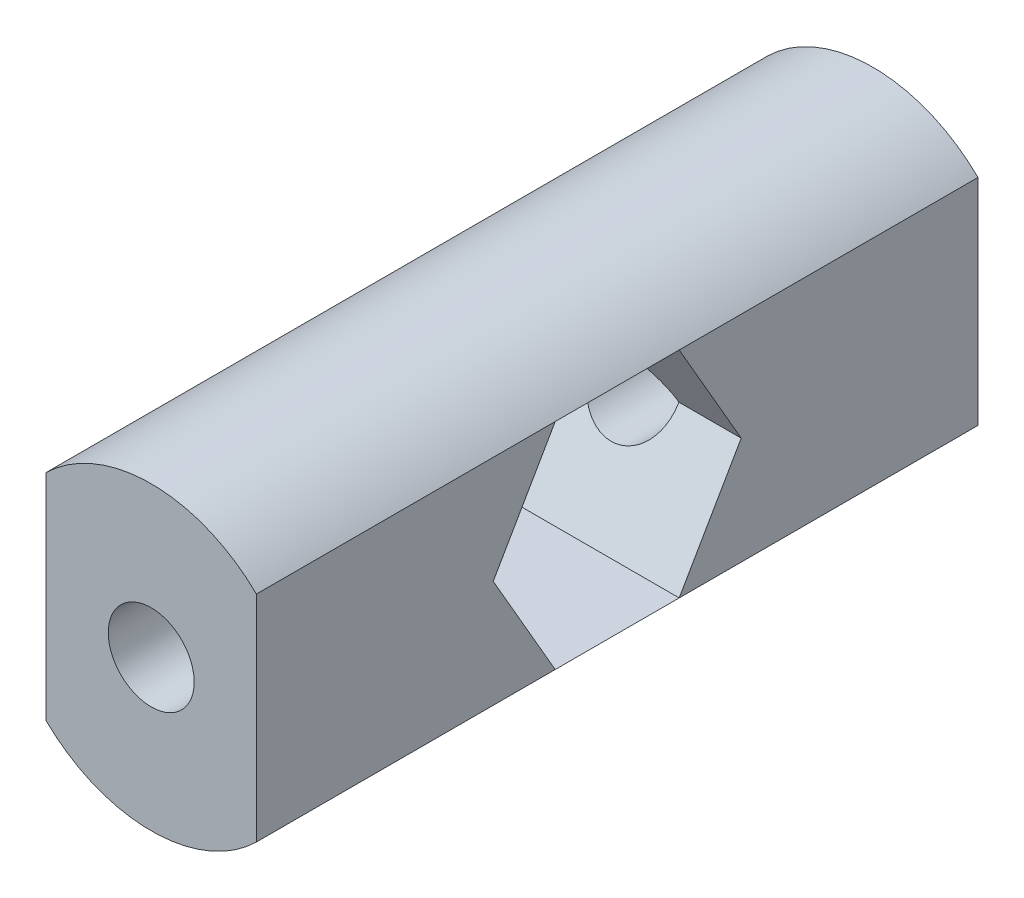
SolidWorks part; units mm, degrees
ref_plane "Front Plane" through (0, 0, 0) normal (0, 0, 1) x (1, 0, 0)
ref_plane "Top Plane" through (0, 0, 0) normal (0, 1, 0) x (1, 0, 0)
ref_plane "Right Plane" through (0, 0, 0) normal (1, 0, 0) x (0, 0, -1)
sketch "Sketch1" plane through (0, 0, 0) normal (0, 0, 1) x (1, 0, 0)
  circle A0 centre (0, 0) radius 17.5
  point P3 (0, 0)
  dimension "D1" = 35
extrude "Boss-Extrude1" add sketch "Sketch1" along normal mid plane 84
sketch "Sketch3" plane through (0, 0, 42) normal (0, 0, 1) x (1, 0, 0)
  line L0 (12.2474, 12.5) -> (12.2474, -12.5) construction
  line L1 (0, 17.5) -> (0, -18.2305) construction
  line L2 (-12.2474, -12.5) -> (-33.4239, -12.5)
  line L3 (12.2474, 12.5) -> (33.4239, 12.5)
  line L4 (12.2474, 12.5) -> (12.2474, -12.5)
  line L5 (12.2474, -12.5) -> (33.4239, -12.5)
  line L6 (33.4239, 12.5) -> (33.4239, -12.5)
  line L7 (-33.4239, 12.5) -> (-33.4239, -12.5)
  line L8 (-12.2474, 12.5) -> (-33.4239, 12.5)
  line L9 (-12.2474, 12.5) -> (-12.2474, -12.5)
  circle A0 centre (0, 0) radius 17.5 construction
  dimension "D1" = 25
extrude "Cut-Extrude1" cut sketch "Sketch3" against normal through all
sketch "Sketch4" plane through (0, 0, 42) normal (0, 0, 1) x (1, 0, 0)
  circle A0 centre (0, 0) radius 5
  dimension "D1" = 10
extrude "Cut-Extrude2" cut sketch "Sketch4" against normal through all
sketch "Sketch5" plane through (12.2474, 0, 0) normal (1, 0, 0) x (0, 0, -1)
  line L1 (14.4338, 0) -> (7.2169, 12.5)
  line L2 (7.2169, 12.5) -> (-7.2169, 12.5)
  line L3 (-7.2169, 12.5) -> (-14.4338, 0)
  line L4 (-14.4338, 0) -> (-7.2169, -12.5)
  line L5 (-7.2169, -12.5) -> (7.2169, -12.5)
  line L6 (7.2169, -12.5) -> (14.4338, 0)
  circle A0 centre (0, 0) radius 12.5 construction
  dimension "D1" = 25
extrude "Cut-Extrude3" cut sketch "Sketch5" against normal blind 74
sketch "Sketch7" plane through (12.2474, 0, 0) normal (1, 0, 0) x (0, 0, -1)
  line L0 (-14.4338, 0) -> (-14.4338, -12.5) construction
  line L1 (-7.2169, -12.5) -> (-42, -12.5) construction
  line L2 (14.4338, 0) -> (14.4338, -12.5) construction
  line L3 (42, -12.5) -> (7.2169, -12.5) construction
  line L4 (-42, 12.5) -> (-42, -12.5) construction
  line L5 (42, 12.5) -> (42, -12.5) construction
  line L6 (-42, 0) -> (42, 0) construction
  dimension "D1" = 27.5662
  dimension "D2" = 27.5662
  dimension "D3" = 28.8675
  dimension "D4" = 84
